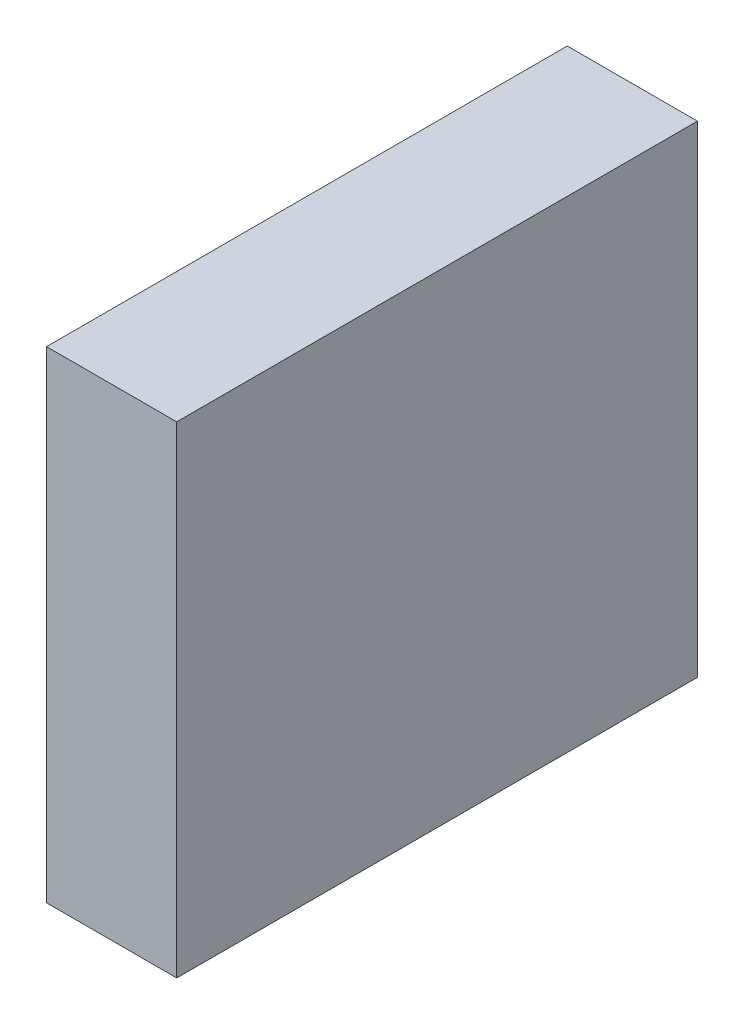
SolidWorks part; units mm, degrees
ref_plane "Front Plane" through (0, 0, 0) normal (0, 0, 1) x (1, 0, 0)
ref_plane "Top Plane" through (0, 0, 0) normal (0, 1, 0) x (1, 0, 0)
ref_plane "Right Plane" through (0, 0, 0) normal (1, 0, 0) x (0, 0, -1)
sketch "Sketch1" plane through (0, 0, 0) normal (1, 0, 0) x (0, 0, -1)
  line L1 (0, 0) -> (40, 0)
  line L2 (0, 0) -> (0, 37)
  line L3 (0, 37) -> (40, 37)
  line L4 (40, 0) -> (40, 37)
extrude "Boss-Extrude1" add sketch "Sketch1" against normal blind 10
